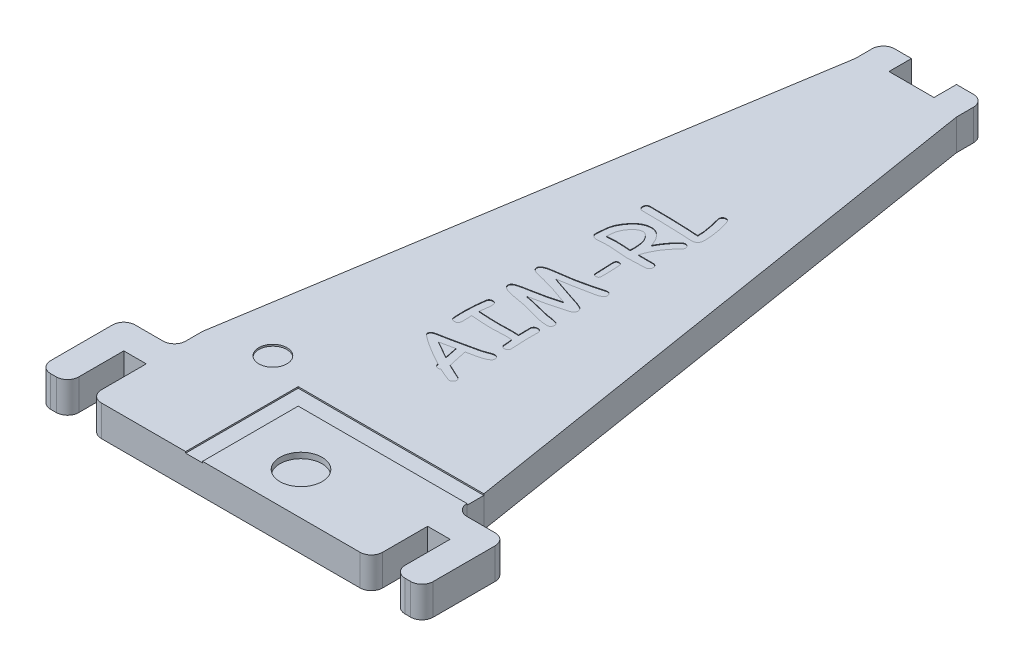
SolidWorks part; units mm, degrees
ref_plane "Front Plane" through (0, 0, 0) normal (0, 0, 1) x (1, 0, 0)
ref_plane "Top Plane" through (0, 0, 0) normal (0, 1, 0) x (1, 0, 0)
ref_plane "Right Plane" through (0, 0, 0) normal (1, 0, 0) x (0, 0, -1)
sketch "Sketch1" plane through (0, 0, 0) normal (0, 1, 0) x (1, 0, 0)
  line L0 (0, 0) -> (0, 1.5)
  line L1 (0, 1.5) -> (0.9, 1.5)
  line L2 (0.9, 1.5) -> (0.9, 2)
  line L3 (0.9, 2) -> (2.5, 12)
  line L4 (2.5, 12) -> (2.5, 12.5)
  line L5 (2.5, 12.5) -> (3, 12.5)
  line L6 (3, 12.5) -> (3, 12.1)
  line L7 (3, 12.1) -> (3.8, 12.1)
  line L8 (3.8, 12.1) -> (3.8, 12.5)
  line L9 (3.8, 12.5) -> (4.3, 12.5)
  line L10 (4.3, 12.5) -> (4.3, 12)
  line L11 (4.3, 12) -> (5.9, 2)
  line L12 (5.9, 2) -> (5.9, 1.5)
  line L13 (5.9, 1.5) -> (6.8, 1.5)
  line L14 (6.8, 1.5) -> (6.8, 0)
  line L15 (6.8, 0) -> (6.3, 0)
  line L16 (6.3, 0) -> (6.3, 1)
  line L17 (6.3, 1) -> (5.9, 1)
  line L18 (5.9, 1) -> (5.9, 0)
  line L19 (5.9, 0) -> (0.9, 0)
  line L20 (0.9, 0) -> (0.9, 1)
  line L21 (0.9, 1) -> (0.5, 1)
  line L22 (0.5, 1) -> (0.5, 0)
  line L23 (0.5, 0) -> (0, 0)
  dimension "D1" = 0.5
  dimension "D2" = 0.4
  dimension "D3" = 0.5
  dimension "D4" = 1.8
  dimension "D5" = 10
  dimension "D6" = 5
  dimension "D7" = 0.5
  dimension "D8" = 1
  dimension "D9" = 0.9
  dimension "D10" = 0.5
  dimension "D11" = 0.4
  dimension "D12" = 0.5
extrude "Boss-Extrude1" add sketch "Sketch1" along normal blind 0.55
fillet "Fillet1" radius 0.2 12 edges at (5.9, 0.275, 0) (6.3, 0.275, 0) (0.5, 0.275, 0) (0.9, 0.275, 0) (0, 0.275, -1.5) (0, 0.275, 0) (6.8, 0.275, 0) (6.8, 0.275, -1.5) (5.9, 0.275, -1.5) (0.9, 0.275, -1.5) (4.3, 0.275, -12.5) (2.5, 0.275, -12.5)
sketch "Sketch3" plane through (0, 0.55, 0) normal (0, 1, 0) x (1, 0, 0)
  line L0 (5.9, 2) -> (2.6, 2)
  line L1 (5.9, 1.7) -> (5.9, 2) construction
  line L2 (2.6, 2) -> (2.6, 0)
  line L3 (1.1, 0) -> (5.7, 0) construction
  line L4 (2.6, 0) -> (2.9, 0)
  line L5 (2.9, 0) -> (2.9, 1.7)
  line L6 (2.9, 1.7) -> (5.9, 1.7)
  line L7 (5.9, 1.7) -> (5.9, 2)
  line L8 (5.9, 0.2) -> (5.9, 1) construction
  arc A0 (5.9, 1.7) -> (6.1, 1.5) centre (6.1, 1.7) ccw construction
  dimension "D1" = 0.3
  dimension "D2" = 0.3
  dimension "D3" = 3
  dimension "D4" = 1.7
extrude "Cut-Extrude1" cut sketch "Sketch3" against normal blind 0.025
sketch "Sketch5" plane through (0, 0.55, 0) normal (0, 1, 0) x (1, 0, 0)
  line L0 (0.9, 2) -> (0.9, 1.7) construction
  line L1 (1.1, 0) -> (2.6, 0) construction
  circle A0 centre (1.9, 2.25) radius 0.25
  dimension "D1" = 0.5
  dimension "D2" = 1
  dimension "D3" = 2.25
extrude "Cut-Extrude3" cut sketch "Sketch5" against normal blind 0.03
sketch "Sketch6" plane through (0, 0.55, 0) normal (0, 1, 0) x (1, 0, 0)
  line L0 (2.9, 0) -> (5.7, 0) construction
  line L1 (5.9, 0.2) -> (5.9, 1) construction
  circle A0 centre (3.9, 0.75) radius 0.375
  dimension "D1" = 0.75
  dimension "D2" = 0.75
  dimension "D3" = 2
extrude "Cut-Extrude4" cut sketch "Sketch6" against normal blind 0.1
sketch "Sketch7" plane through (0, 0.55, 0) normal (0, 1, 0) x (1, 0, 0)
  line L1 (3.9, 12.1) -> (3.9, -0.3336) construction
  text T0 "AIM-RL" font "Comic Sans MS" height 1
extrude "Cut-Extrude5" cut sketch "Sketch7" against normal blind 0.01
